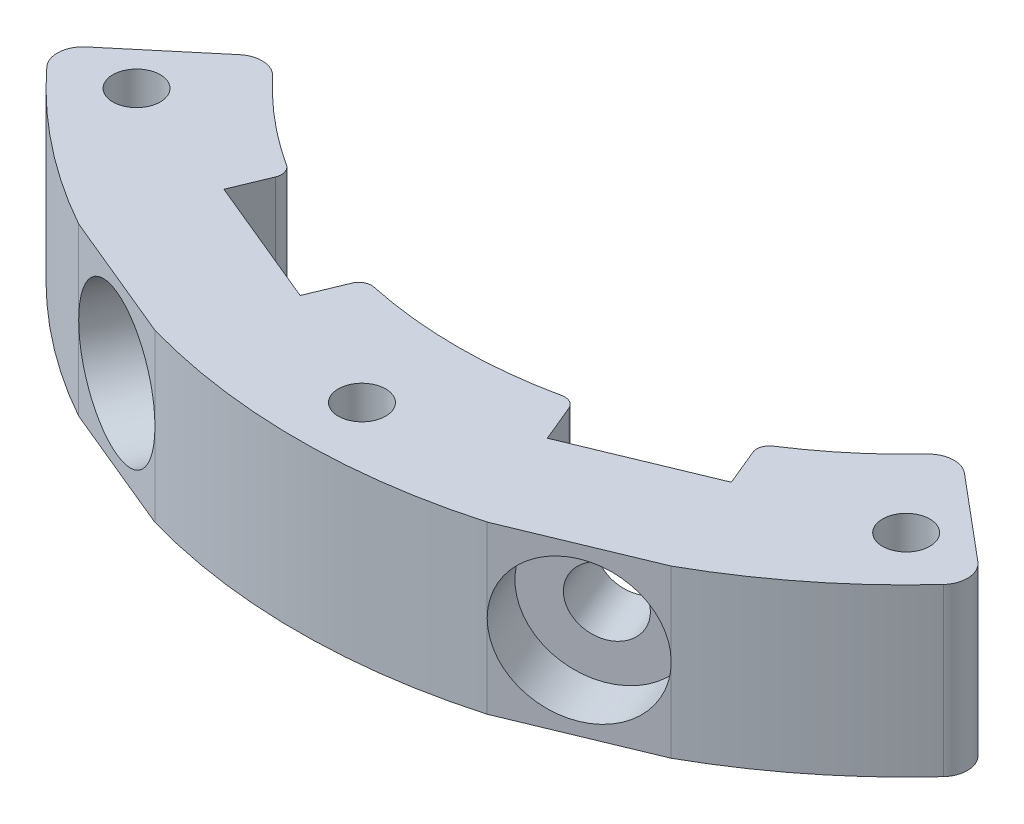
SolidWorks part; units mm, degrees
ref_plane "前视基准面" through (0, 0, 0) normal (0, 0, 1) x (1, 0, 0)
ref_plane "上视基准面" through (0, 0, 0) normal (0, 1, 0) x (1, 0, 0)
ref_plane "右视基准面" through (0, 0, 0) normal (1, 0, 0) x (0, 0, -1)
other "Configuration Table"
sketch "草图1" plane through (0, 0, 0) normal (0, 1, 0) x (1, 0, 0)
  line L0 (0, 0) -> (-42.5, 0) construction
  line L1 (0, 0) -> (0, -42.5) construction
  line L2 (0, 0) -> (-32.5569, -27.3185) construction
  line L3 (-26.8116, -22.4976) -> (-36.3871, -30.5324)
  line L4 (0, 0) -> (-15.026, -36.276) construction
  line L5 (-30.052, -30.052) -> (0, -42.5)
  line L6 (-18.3088, -29.8293) -> (-19.8146, -33.4646)
  line L7 (-19.8146, -33.4646) -> (-9.652, -37.6741)
  line L8 (-9.652, -37.6741) -> (-8.1462, -34.0388)
  line L9 (9.652, -37.6741) -> (8.1462, -34.0388)
  line L10 (19.8146, -33.4646) -> (9.652, -37.6741)
  line L11 (18.3088, -29.8293) -> (19.8146, -33.4646)
  line L12 (26.8116, -22.4976) -> (36.3871, -30.5324)
  circle A0 centre (0, 0) radius 42.5 construction
  circle A1 centre (0, -42.5) radius 1.85
  circle A2 centre (0, 0) radius 35
  circle A3 centre (0, 0) radius 47.5
  circle A4 centre (-30.052, -30.052) radius 1.85
  circle A5 centre (30.052, -30.052) radius 1.85
  point P18 (-14.7333, -35.5694)
  dimension "D1" = 85
  dimension "D2" = 3.7
  dimension "D4" = 95
  dimension "D5" = 70
  dimension "D7" = 3.7
  dimension "D3" = 40
  dimension "D6" = 22.5
  dimension "D8" = 38.5
  dimension "D9" = 11
extrude "凸台-拉伸1" add sketch "草图1" along normal blind 13
sketch "草图2" plane through (-14.7333, 0, 35.5694) normal (0.3827, 0, -0.9239) x (-0.9239, 0, -0.3827)
  line L0 (0, 13) -> (0, 0) construction
  line L1 (-5.5, 6.5) -> (5.5, 6.5) construction
  line L4 (-5.5, 0) -> (5.5, 0)
  line L5 (5.5, 0) -> (5.5, 13)
  line L6 (5.5, 13) -> (-5.5, 13)
  line L7 (-5.5, 13) -> (-5.5, 0)
  line L8 (-5.5, 0) -> (5.5, 0)
  line L9 (5.5, 0) -> (5.5, 13)
  line L10 (5.5, 13) -> (-5.5, 13)
  line L11 (-5.5, 13) -> (-5.5, 0)
  circle A0 centre (0, 6.5) radius 2.6
  dimension "D2" = 5.2
  dimension "D1" = 0
extrude "切除-拉伸1" cut sketch "草图2" against normal blind 10 contours A0
sketch "草图3" plane through (14.7333, 0, 35.5694) normal (-0.3827, 0, -0.9239) x (-0.9239, 0, 0.3827)
  line L0 (0, 13) -> (0, 0) construction
  line L1 (-5.5, 6.5) -> (5.5, 6.5) construction
  line L4 (-5.5, 0) -> (5.5, 0)
  line L5 (5.5, 0) -> (5.5, 13)
  line L6 (5.5, 13) -> (-5.5, 13)
  line L7 (-5.5, 13) -> (-5.5, 0)
  line L8 (-5.5, 0) -> (5.5, 0)
  line L9 (5.5, 0) -> (5.5, 13)
  line L10 (5.5, 13) -> (-5.5, 13)
  line L11 (-5.5, 13) -> (-5.5, 0)
  circle A0 centre (0, 6.5) radius 2.6
  dimension "D2" = 5.2
  dimension "D1" = 0
extrude "切除-拉伸2" cut sketch "草图3" against normal blind 10 contours A0
fillet "圆角1" radius 2 4 edges at (26.8116, 6.5, 22.4976) (36.3871, 6.5, 30.5324) (-26.8116, 6.5, 22.4976) (-36.3871, 6.5, 30.5324)
fillet "圆角2" radius 1 4 edges at (-8.1462, 6.5, 34.0388) (-18.3088, 6.5, 29.8293) (18.3088, 6.5, 29.8293) (8.1462, 6.5, 34.0388)
sketch "草图4" plane through (0, 0, 0) normal (0, -1, 0) x (1, 0, 0)
  circle A0 centre (-30.052, 30.052) radius 3.5
  circle A1 centre (0, 42.5) radius 1.85
  circle A2 centre (0, 42.5) radius 1.85
  circle A3 centre (-30.052, 30.052) radius 1.85
  circle A4 centre (-30.052, 30.052) radius 1.85
  circle A5 centre (30.052, 30.052) radius 1.85
  circle A6 centre (30.052, 30.052) radius 1.85
  circle A7 centre (0, 42.5) radius 3.5
  circle A8 centre (30.052, 30.052) radius 3.5
  dimension "D4" = 7
  dimension "D5" = 7
  dimension "D6" = 7
  dimension "D1" = 0
  dimension "D2" = 0
  dimension "D3" = 0
extrude "切除-拉伸3" cut sketch "草图4" against normal blind 7
sketch "草图5" plane through (0, 0, 0) normal (0, -1, 0) x (1, 0, 0)
  line L0 (-14.7333, 35.5694) -> (-18.1775, 43.8843)
  line L1 (14.7333, 35.5694) -> (18.1775, 43.8843)
  line L2 (-23.1365, 41.4843) -> (-12.9739, 45.6939)
  line L3 (-19.8146, 33.4646) -> (-23.1365, 41.4843)
  line L4 (-9.652, 37.6741) -> (-12.9739, 45.6939)
  line L5 (0, 42.5) -> (0, 0)
  line L6 (23.1365, 41.4843) -> (12.9739, 45.6939)
  line L8 (-9.652, 37.6741) -> (-8.4688, 34.8178)
  line L9 (8.4688, 34.8178) -> (9.652, 37.6741)
  line L10 (9.652, 37.6741) -> (19.8146, 33.4646)
  line L11 (19.8146, 33.4646) -> (18.6315, 30.6083)
  line L12 (28.3022, 23.7484) -> (34.8213, 29.2186)
  line L13 (-34.8213, 29.2186) -> (-28.3022, 23.7484)
  line L14 (-18.6315, 30.6083) -> (-19.8146, 33.4646)
  line L15 (-19.8146, 33.4646) -> (-9.652, 37.6741)
  line L16 (-9.652, 37.6741) -> (-8.4688, 34.8178)
  line L17 (8.4688, 34.8178) -> (9.652, 37.6741)
  line L18 (9.652, 37.6741) -> (19.8146, 33.4646)
  line L19 (19.8146, 33.4646) -> (18.6315, 30.6083)
  line L20 (28.3022, 23.7484) -> (34.8213, 29.2186)
  line L21 (-34.8213, 29.2186) -> (-28.3022, 23.7484)
  line L22 (-18.6315, 30.6083) -> (-19.8146, 33.4646)
  line L23 (-19.8146, 33.4646) -> (-9.652, 37.6741)
  arc A0 (35.0099, 32.1023) -> (-35.0099, 32.1023) centre (0, 0) ccw construction
  arc A12 (-8.4688, 34.8178) -> (-7.3354, 34.2227) centre (-7.545, 35.2005) ccw
  arc A13 (7.3354, 34.2227) -> (-7.3354, 34.2227) centre (0, 0) ccw
  arc A14 (7.3354, 34.2227) -> (8.4688, 34.8178) centre (7.545, 35.2005) ccw
  arc A15 (18.6315, 30.6083) -> (19.0122, 29.386) centre (19.5554, 30.2256) ccw
  arc A16 (25.5563, 23.9139) -> (19.0122, 29.386) centre (0, 0) ccw
  arc A17 (25.5563, 23.9139) -> (28.3022, 23.7484) centre (27.0166, 25.2805) ccw
  arc A18 (34.8213, 29.2186) -> (35.0099, 32.1023) centre (33.5358, 30.7507) ccw
  arc A19 (35.0099, 32.1023) -> (-35.0099, 32.1023) centre (0, 0) ccw
  arc A20 (-35.0099, 32.1023) -> (-34.8213, 29.2186) centre (-33.5358, 30.7507) ccw
  arc A21 (-28.3022, 23.7484) -> (-25.5563, 23.9139) centre (-27.0166, 25.2805) ccw
  arc A22 (-19.0122, 29.386) -> (-25.5563, 23.9139) centre (0, 0) ccw
  arc A23 (-19.0122, 29.386) -> (-18.6315, 30.6083) centre (-19.5554, 30.2256) ccw
  arc A24 (-8.4688, 34.8178) -> (-7.3354, 34.2227) centre (-7.545, 35.2005) ccw
  arc A25 (7.3354, 34.2227) -> (-7.3354, 34.2227) centre (0, 0) ccw
  arc A26 (7.3354, 34.2227) -> (8.4688, 34.8178) centre (7.545, 35.2005) ccw
  arc A27 (18.6315, 30.6083) -> (19.0122, 29.386) centre (19.5554, 30.2256) ccw
  arc A28 (25.5563, 23.9139) -> (19.0122, 29.386) centre (0, 0) ccw
  arc A29 (25.5563, 23.9139) -> (28.3022, 23.7484) centre (27.0166, 25.2805) ccw
  arc A30 (34.8213, 29.2186) -> (35.0099, 32.1023) centre (33.5358, 30.7507) ccw
  arc A31 (35.0099, 32.1023) -> (-35.0099, 32.1023) centre (0, 0) ccw
  arc A32 (-35.0099, 32.1023) -> (-34.8213, 29.2186) centre (-33.5358, 30.7507) ccw
  arc A33 (-28.3022, 23.7484) -> (-25.5563, 23.9139) centre (-27.0166, 25.2805) ccw
  arc A34 (-19.0122, 29.386) -> (-25.5563, 23.9139) centre (0, 0) ccw
  arc A35 (-19.0122, 29.386) -> (-18.6315, 30.6083) centre (-19.5554, 30.2256) ccw
  arc M39 (35.0099, 32.1023) -> (-35.0099, 32.1023) centre (0, 0) ccw
  dimension "D1" = 0
extrude "切除-拉伸5" cut sketch "草图5" against normal through all contours L2 L0 M39 | L0 L2 M39 | L6 L1 M39 | L6 L1 M39
sketch "草图6" plane through (-18.0552, 0, 43.5891) normal (-0.3827, 0, 0.9239) x (0.9239, 0, 0.3827)
  circle A0 centre (0, 6.5) radius 2.6 construction
  circle A1 centre (0, 6.5) radius 2.6
  circle A2 centre (0, 6.5) radius 5.5
  dimension "D1" = 11
extrude "切除-拉伸6" cut sketch "草图6" against normal blind 4
sketch "草图7" plane through (18.0552, 0, 43.5891) normal (0.3827, 0, 0.9239) x (0.9239, 0, -0.3827)
  circle A0 centre (0, 6.5) radius 2.6 construction
  circle A1 centre (0, 6.5) radius 2.6
  circle A2 centre (0, 6.5) radius 5.5
  dimension "D1" = 11
extrude "切除-拉伸7" cut sketch "草图7" against normal blind 4
